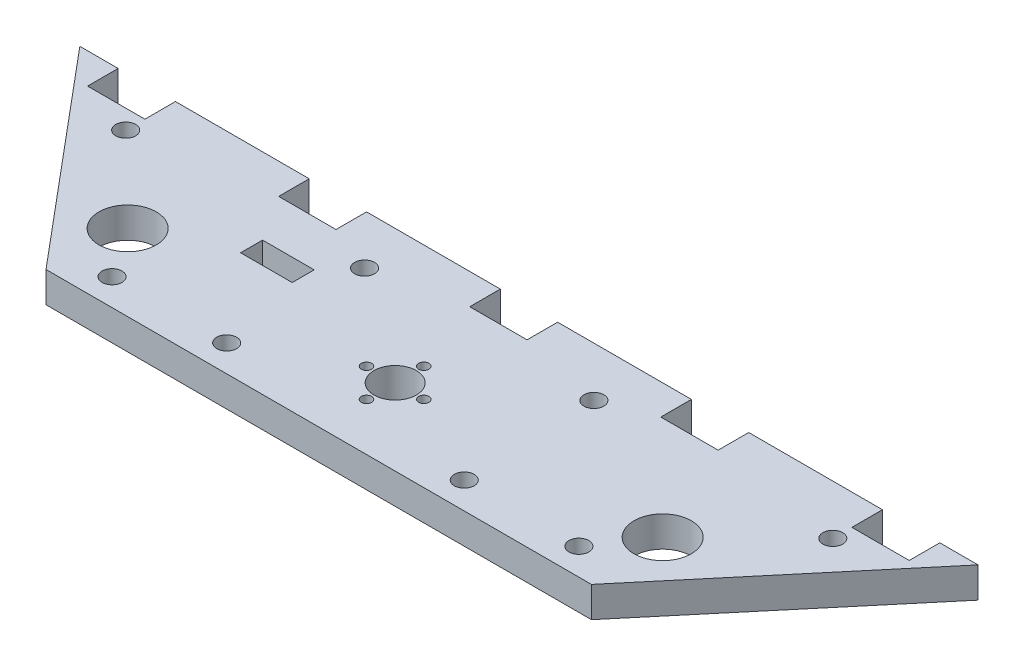
SolidWorks part; units mm, degrees
ref_plane "Ön Düzlem" through (0, 0, 0) normal (0, 0, 1) x (1, 0, 0)
ref_plane "Üst Düzlem" through (0, 0, 0) normal (0, 1, 0) x (1, 0, 0)
ref_plane "Sağ Düzlem" through (0, 0, 0) normal (1, 0, 0) x (0, 0, -1)
sketch "Çizim1" plane through (0, 0, 0) normal (0, 1, 0) x (1, 0, 0)
  line L5 (-41.9507, 34.2338) -> (-28.4507, 34.2338)
  line L6 (-63.6239, -0.7662) -> (-109.7744, 54.2338)
  line L13 (79.1057, -0.7662) -> (125.2562, 54.2338)
  line L14 (-41.9507, 34.2338) -> (-41.9507, 28.4838)
  line L15 (-41.9507, 28.4838) -> (-28.4507, 28.4838)
  line L16 (-28.4507, 34.2338) -> (-28.4507, 28.4838)
  line L17 (7.7409, -0.7662) -> (79.1057, -0.7662)
  line L18 (7.7409, 54.2338) -> (-109.7744, 54.2338)
  line L19 (-109.7744, 54.2338) -> (125.2562, 54.2338)
  line L20 (79.1057, -0.7662) -> (-63.6239, -0.7662)
  circle A0 centre (-62.2591, 19.2338) radius 7.5
  circle A1 centre (77.7409, 19.2338) radius 7.5
  circle A4 centre (-53.3383, 6.2338) radius 2.6821
  circle A5 centre (-23.3383, 6.2338) radius 2.7804
  circle A10 centre (7.7409, 19.2338) radius 5.1875
  circle A11 centre (-84.7744, 41.2338) radius 3.6026
  circle A12 centre (-22.2591, 41.2338) radius 4.0418
  circle A15 centre (100.2562, 41.2338) radius 3.6026
  circle A16 centre (37.7409, 41.2338) radius 4.0418
  circle A17 centre (68.8202, 6.2338) radius 2.6821
  circle A18 centre (38.8202, 6.2338) radius 2.7804
  dimension "D3" = 5.75
  dimension "D4" = 25
  dimension "D5" = 15
  dimension "D6" = 13
  dimension "D8" = 13
  dimension "D9" = 13
  dimension "D13" = 30
  dimension "D7" = 13
  dimension "D2" = 13.5
extrude "Yükseklik-Ekstrüzyon1" add sketch "Çizim1" along normal blind 8 contours L20 L17 L13 L19 L18 L6 A17 A15 A12 A11 A10 A5 A4 L5 L16 L15 L14 A0 A1 A16 A18 | A11 | A12 | A16 | A15 | A17 | A18 | A4 | A5
hole_wizard "M5 Helisarmal için Zıvana matkabı2" positions "Çizim11" profile "Çizim12" hole size "M5x0.8" standard "ANSI Metric" end condition up to next
sketch "Çizim11" plane through (0, 0, 0) normal (0, -1, 0) x (-1, 0, 0)
  point P0 (-68.8202, 6.2338)
  point P3 (-38.8202, 6.2338)
  point P6 (-37.7409, 41.2338)
  point P9 (-100.2562, 41.2338)
  point P12 (22.2591, 41.2338)
  point P15 (23.3383, 6.2338)
  point P18 (53.3383, 6.2338)
  point P21 (84.7744, 41.2338)
sketch "Çizim12" plane through (68.8202, 0, -6.2338) normal (1, 0, 0) x (0, 0, -1)
  line L0 (0, 0) -> (0, 8)
  line L1 (0, 8) -> (2.6, 8)
  line L2 (2.6, 8) -> (2.6, 0)
  line L5 (2.6, 0) -> (0, 0)
  line L11 (0, -6.35) -> (0, 107.95) construction
  dimension "Thru Hole Dia." = 5.2
  dimension "Thru Hole Depth" = 8
sketch "Çizim13" plane through (0, 0, 0) normal (0, -1, 0) x (1, 0, 0)
  circle A0 centre (7.7409, -19.2338) radius 5.55
  circle A1 centre (15.2409, -19.2338) radius 1.35
  circle A2 centre (7.7409, -26.7338) radius 1.35
  circle A3 centre (0.2409, -19.2338) radius 1.35
  circle A4 centre (7.7409, -11.7338) radius 1.35
extrude "Kes-Ekstrüzyon5" cut sketch "Çizim13" against normal blind 10
sketch "Çizim14" plane through (0, 0, -54.2338) normal (0, 0, -1) x (-1, 0, 0)
  line L0 (-65.2562, 8) -> (-65.2562, 0)
  line L1 (-125.2562, 8) -> (109.7744, 8)
  line L2 (-125.2562, 8) -> (-125.2562, 0)
  line L3 (-125.2562, 0) -> (109.7744, 0)
  line L4 (109.7744, 8) -> (109.7744, 0)
  line L5 (-115.2562, 8) -> (-100.2562, 8)
  line L6 (-115.2562, 8) -> (-115.2562, 0)
  line L7 (-115.2562, 0) -> (-100.2562, 0)
  line L8 (-100.2562, 8) -> (-100.2562, 0)
  line L9 (-65.2562, 8) -> (-50.2562, 8)
  line L10 (-50.2562, 8) -> (-50.2562, 0)
  line L11 (-65.2562, 0) -> (-50.2562, 0)
  line L12 (-15.2562, 8) -> (-15.2562, 0)
  line L13 (-15.2562, 8) -> (-0.2562, 8)
  line L14 (-0.2562, 8) -> (-0.2562, 0)
  line L15 (-15.2562, 0) -> (-0.2562, 0)
  line L16 (34.7438, 8) -> (34.7438, 0)
  line L17 (34.7438, 8) -> (49.7438, 8)
  line L18 (49.7438, 8) -> (49.7438, 0)
  line L19 (34.7438, 0) -> (49.7438, 0)
  line L20 (84.7438, 8) -> (84.7438, 0)
  line L21 (84.7438, 8) -> (99.7438, 8)
  line L22 (99.7438, 8) -> (99.7438, 0)
  line L23 (84.7438, 0) -> (99.7438, 0)
  line M9 (-125.2562, 0) -> (109.7744, 0)
  dimension "D1" = 10
  dimension "D2" = 15
  dimension "D3" = 5
extrude "Kes-Ekstrüzyon6" cut sketch "Çizim14" against normal blind 8 contours L8 L1 L6 L3 | L10 L1 L0 M9 | L14 L1 L12 M9 | L18 L1 L16 M9 | L22 L1 L20 M9
